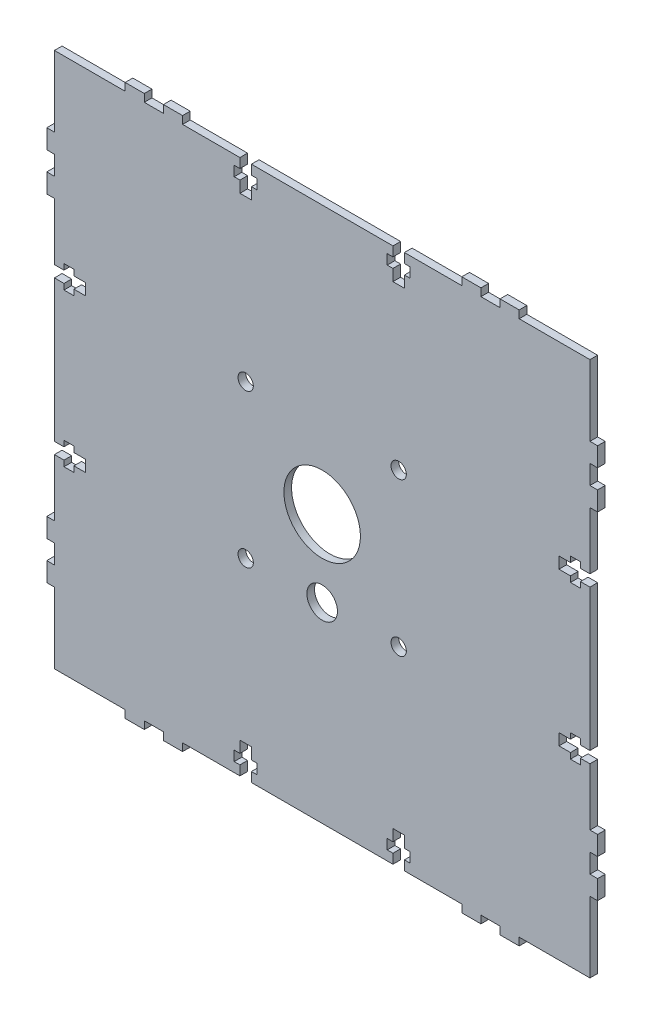
SolidWorks part; units mm, degrees
ref_plane "前视基准面" through (0, 0, 0) normal (0, 0, 1) x (1, 0, 0)
ref_plane "上视基准面" through (0, 0, 0) normal (0, 1, 0) x (1, 0, 0)
ref_plane "右视基准面" through (0, 0, 0) normal (1, 0, 0) x (0, 0, -1)
sketch "草图1" plane through (0, 0, 0) normal (0, 0, 1) x (1, 0, 0)
  line L50 (249.9534, 275.9629) -> (249.9534, 255.9629) construction
  line L53 (317.4534, 257.4629) -> (317.4534, 258.9629)
  line L54 (317.4534, 254.4629) -> (317.4534, 252.9629)
  line L55 (319.9534, 254.4629) -> (317.4534, 254.4629)
  line L56 (317.4534, 258.9629) -> (314.8534, 258.9629)
  line L57 (314.8534, 258.9629) -> (314.8534, 257.4629)
  line L58 (314.8534, 257.4629) -> (311.8534, 257.4629)
  line L59 (311.8534, 254.4629) -> (311.8534, 257.4629)
  line L60 (314.8534, 254.4629) -> (311.8534, 254.4629)
  line L61 (314.8534, 252.9629) -> (314.8534, 254.4629)
  line L62 (317.4534, 252.9629) -> (314.8534, 252.9629)
  line L63 (317.4534, 257.4629) -> (319.9534, 257.4629)
  line L68 (319.9534, 254.4629) -> (319.9534, 257.4629) construction
  line L69 (311.8534, 255.9629) -> (319.9534, 255.9629) construction
  line L73 (311.8534, 295.9629) -> (319.9534, 295.9629) construction
  line L75 (317.4534, 294.4629) -> (319.9534, 294.4629)
  line L76 (317.4534, 298.9629) -> (314.8534, 298.9629)
  line L77 (314.8534, 298.9629) -> (314.8534, 297.4629)
  line L78 (314.8534, 297.4629) -> (311.8534, 297.4629)
  line L79 (311.8534, 297.4629) -> (311.8534, 294.4629)
  line L80 (314.8534, 294.4629) -> (311.8534, 294.4629)
  line L81 (314.8534, 292.9629) -> (314.8534, 294.4629)
  line L82 (317.4534, 292.9629) -> (314.8534, 292.9629)
  line L83 (319.9534, 297.4629) -> (317.4534, 297.4629)
  line L84 (317.4534, 297.4629) -> (317.4534, 298.9629)
  line L85 (317.4534, 294.4629) -> (317.4534, 292.9629)
  line L86 (231.4534, 208.4629) -> (232.9534, 208.4629)
  line L87 (228.4534, 208.4629) -> (226.9534, 208.4629)
  line L88 (228.4534, 205.9629) -> (228.4534, 208.4629)
  line L89 (232.9534, 208.4629) -> (232.9534, 211.0629)
  line L90 (232.9534, 211.0629) -> (231.4534, 211.0629)
  line L91 (231.4534, 211.0629) -> (231.4534, 214.0629)
  line L92 (228.4534, 214.0629) -> (231.4534, 214.0629)
  line L93 (228.4534, 211.0629) -> (228.4534, 214.0629)
  line L94 (226.9534, 211.0629) -> (228.4534, 211.0629)
  line L95 (226.9534, 208.4629) -> (226.9534, 211.0629)
  line L96 (231.4534, 208.4629) -> (231.4534, 205.9629)
  line L97 (268.4534, 208.4629) -> (268.4534, 205.9629)
  line L98 (272.9534, 208.4629) -> (272.9534, 211.0629)
  line L99 (272.9534, 211.0629) -> (271.4534, 211.0629)
  line L100 (271.4534, 211.0629) -> (271.4534, 214.0629)
  line L101 (271.4534, 214.0629) -> (268.4534, 214.0629)
  line L102 (268.4534, 211.0629) -> (268.4534, 214.0629)
  line L103 (266.9534, 211.0629) -> (268.4534, 211.0629)
  line L104 (266.9534, 208.4629) -> (266.9534, 211.0629)
  line L105 (271.4534, 205.9629) -> (271.4534, 208.4629)
  line L106 (271.4534, 208.4629) -> (272.9534, 208.4629)
  line L107 (268.4534, 208.4629) -> (266.9534, 208.4629)
  line L108 (228.4534, 205.9629) -> (231.4534, 205.9629) construction
  line L109 (229.9534, 214.0629) -> (229.9534, 205.9629) construction
  line L110 (269.9534, 214.0629) -> (269.9534, 205.9629) construction
  line L111 (182.4534, 294.4629) -> (182.4534, 292.9629)
  line L112 (182.4534, 297.4629) -> (182.4534, 298.9629)
  line L113 (179.9534, 297.4629) -> (182.4534, 297.4629)
  line L114 (182.4534, 292.9629) -> (185.0534, 292.9629)
  line L115 (185.0534, 292.9629) -> (185.0534, 294.4629)
  line L116 (185.0534, 294.4629) -> (188.0534, 294.4629)
  line L117 (188.0534, 297.4629) -> (188.0534, 294.4629)
  line L118 (185.0534, 297.4629) -> (188.0534, 297.4629)
  line L119 (185.0534, 298.9629) -> (185.0534, 297.4629)
  line L120 (182.4534, 298.9629) -> (185.0534, 298.9629)
  line L121 (182.4534, 294.4629) -> (179.9534, 294.4629)
  line L122 (182.4534, 257.4629) -> (179.9534, 257.4629)
  line L123 (182.4534, 252.9629) -> (185.0534, 252.9629)
  line L124 (185.0534, 252.9629) -> (185.0534, 254.4629)
  line L125 (185.0534, 254.4629) -> (188.0534, 254.4629)
  line L126 (188.0534, 254.4629) -> (188.0534, 257.4629)
  line L127 (185.0534, 257.4629) -> (188.0534, 257.4629)
  line L128 (185.0534, 258.9629) -> (185.0534, 257.4629)
  line L129 (182.4534, 258.9629) -> (185.0534, 258.9629)
  line L130 (179.9534, 254.4629) -> (182.4534, 254.4629)
  line L131 (182.4534, 254.4629) -> (182.4534, 252.9629)
  line L132 (182.4534, 257.4629) -> (182.4534, 258.9629)
  line L133 (179.9534, 297.4629) -> (179.9534, 294.4629) construction
  line L134 (188.0534, 295.9629) -> (179.9534, 295.9629) construction
  line L135 (188.0534, 255.9629) -> (179.9534, 255.9629) construction
  line L136 (268.4534, 343.4629) -> (266.9534, 343.4629)
  line L137 (271.4534, 343.4629) -> (272.9534, 343.4629)
  line L138 (271.4534, 345.9629) -> (271.4534, 343.4629)
  line L139 (266.9534, 343.4629) -> (266.9534, 340.8629)
  line L140 (266.9534, 340.8629) -> (268.4534, 340.8629)
  line L141 (268.4534, 340.8629) -> (268.4534, 337.8629)
  line L142 (271.4534, 337.8629) -> (268.4534, 337.8629)
  line L143 (271.4534, 340.8629) -> (271.4534, 337.8629)
  line L144 (272.9534, 340.8629) -> (271.4534, 340.8629)
  line L145 (272.9534, 343.4629) -> (272.9534, 340.8629)
  line L146 (268.4534, 343.4629) -> (268.4534, 345.9629)
  line L147 (231.4534, 343.4629) -> (231.4534, 345.9629)
  line L148 (226.9534, 343.4629) -> (226.9534, 340.8629)
  line L149 (226.9534, 340.8629) -> (228.4534, 340.8629)
  line L150 (228.4534, 340.8629) -> (228.4534, 337.8629)
  line L151 (228.4534, 337.8629) -> (231.4534, 337.8629)
  line L152 (231.4534, 340.8629) -> (231.4534, 337.8629)
  line L153 (232.9534, 340.8629) -> (231.4534, 340.8629)
  line L154 (232.9534, 343.4629) -> (232.9534, 340.8629)
  line L155 (228.4534, 345.9629) -> (228.4534, 343.4629)
  line L156 (228.4534, 343.4629) -> (226.9534, 343.4629)
  line L157 (231.4534, 343.4629) -> (232.9534, 343.4629)
  line L158 (271.4534, 345.9629) -> (268.4534, 345.9629) construction
  line L159 (269.9534, 337.8629) -> (269.9534, 345.9629) construction
  line L160 (229.9534, 337.8629) -> (229.9534, 345.9629) construction
  line L163 (179.9534, 294.4629) -> (179.9534, 257.4629)
  line L169 (268.4534, 345.9629) -> (231.4534, 345.9629)
  line L172 (319.9534, 257.4629) -> (319.9534, 294.4629)
  line L175 (231.4534, 205.9629) -> (268.4534, 205.9629)
  line L188 (179.9534, 239.4629) -> (177.9534, 239.4629)
  line L189 (177.9534, 239.4629) -> (177.9534, 234.4629)
  line L190 (177.9534, 234.4629) -> (179.9534, 234.4629)
  line L191 (179.9534, 234.4629) -> (179.9534, 229.4629)
  line L192 (179.9534, 229.4629) -> (177.9534, 229.4629)
  line L193 (177.9534, 229.4629) -> (177.9534, 224.4629)
  line L194 (177.9534, 224.4629) -> (179.9534, 224.4629)
  line L195 (179.9534, 224.4629) -> (179.9534, 205.9629)
  line L196 (179.9534, 327.4629) -> (179.9534, 345.9629)
  line L197 (177.9534, 327.4629) -> (179.9534, 327.4629)
  line L198 (177.9534, 322.4629) -> (177.9534, 327.4629)
  line L199 (179.9534, 322.4629) -> (177.9534, 322.4629)
  line L200 (179.9534, 317.4629) -> (179.9534, 322.4629)
  line L201 (177.9534, 317.4629) -> (179.9534, 317.4629)
  line L202 (177.9534, 312.4629) -> (177.9534, 317.4629)
  line L203 (179.9534, 312.4629) -> (177.9534, 312.4629)
  line L206 (213.4534, 345.9629) -> (213.4534, 347.9629)
  line L207 (213.4534, 347.9629) -> (208.4534, 347.9629)
  line L208 (208.4534, 347.9629) -> (208.4534, 345.9629)
  line L209 (208.4534, 345.9629) -> (203.4534, 345.9629)
  line L210 (203.4534, 345.9629) -> (203.4534, 347.9629)
  line L211 (203.4534, 347.9629) -> (198.4534, 347.9629)
  line L212 (198.4534, 347.9629) -> (198.4534, 345.9629)
  line L213 (198.4534, 345.9629) -> (179.9534, 345.9629)
  line L214 (301.4534, 345.9629) -> (319.9534, 345.9629)
  line L215 (301.4534, 347.9629) -> (301.4534, 345.9629)
  line L216 (296.4534, 347.9629) -> (301.4534, 347.9629)
  line L217 (296.4534, 345.9629) -> (296.4534, 347.9629)
  line L218 (291.4534, 345.9629) -> (296.4534, 345.9629)
  line L219 (291.4534, 347.9629) -> (291.4534, 345.9629)
  line L220 (286.4534, 347.9629) -> (291.4534, 347.9629)
  line L221 (286.4534, 345.9629) -> (286.4534, 347.9629)
  line L224 (319.9534, 312.4629) -> (321.9534, 312.4629)
  line L225 (321.9534, 312.4629) -> (321.9534, 317.4629)
  line L226 (321.9534, 317.4629) -> (319.9534, 317.4629)
  line L227 (319.9534, 317.4629) -> (319.9534, 322.4629)
  line L228 (319.9534, 322.4629) -> (321.9534, 322.4629)
  line L229 (321.9534, 322.4629) -> (321.9534, 327.4629)
  line L230 (321.9534, 327.4629) -> (319.9534, 327.4629)
  line L231 (319.9534, 327.4629) -> (319.9534, 345.9629)
  line L232 (319.9534, 224.4629) -> (319.9534, 205.9629)
  line L233 (321.9534, 224.4629) -> (319.9534, 224.4629)
  line L234 (321.9534, 229.4629) -> (321.9534, 224.4629)
  line L235 (319.9534, 229.4629) -> (321.9534, 229.4629)
  line L236 (319.9534, 234.4629) -> (319.9534, 229.4629)
  line L237 (321.9534, 234.4629) -> (319.9534, 234.4629)
  line L238 (321.9534, 239.4629) -> (321.9534, 234.4629)
  line L239 (319.9534, 239.4629) -> (321.9534, 239.4629)
  line L242 (286.4534, 205.9629) -> (286.4534, 203.9629)
  line L243 (286.4534, 203.9629) -> (291.4534, 203.9629)
  line L244 (291.4534, 203.9629) -> (291.4534, 205.9629)
  line L245 (291.4534, 205.9629) -> (296.4534, 205.9629)
  line L246 (296.4534, 205.9629) -> (296.4534, 203.9629)
  line L247 (296.4534, 203.9629) -> (301.4534, 203.9629)
  line L248 (301.4534, 203.9629) -> (301.4534, 205.9629)
  line L249 (301.4534, 205.9629) -> (319.9534, 205.9629)
  line L250 (198.4534, 205.9629) -> (179.9534, 205.9629)
  line L251 (198.4534, 203.9629) -> (198.4534, 205.9629)
  line L252 (203.4534, 203.9629) -> (198.4534, 203.9629)
  line L253 (203.4534, 205.9629) -> (203.4534, 203.9629)
  line L254 (208.4534, 205.9629) -> (203.4534, 205.9629)
  line L255 (208.4534, 203.9629) -> (208.4534, 205.9629)
  line L256 (213.4534, 203.9629) -> (208.4534, 203.9629)
  line L257 (213.4534, 205.9629) -> (213.4534, 203.9629)
  line L261 (249.9534, 255.9629) -> (229.9534, 255.9629) construction
  line L268 (179.9534, 297.4629) -> (179.9534, 312.4629)
  line L269 (213.4534, 345.9629) -> (228.4534, 345.9629)
  line L270 (271.4534, 345.9629) -> (286.4534, 345.9629)
  line L271 (319.9534, 312.4629) -> (319.9534, 297.4629)
  line L272 (319.9534, 254.4629) -> (319.9534, 239.4629)
  line L273 (286.4534, 205.9629) -> (271.4534, 205.9629)
  line L274 (213.4534, 205.9629) -> (228.4534, 205.9629)
  line L275 (179.9534, 239.4629) -> (179.9534, 254.4629)
  circle A14 centre (249.9534, 275.9629) radius 10
  circle A24 centre (249.9534, 255.9629) radius 4
  circle A29 centre (229.9534, 255.9629) radius 2
  circle A30 centre (229.9534, 295.9629) radius 2
  circle A31 centre (269.9534, 295.9629) radius 2
  circle A32 centre (269.9534, 255.9629) radius 2
  dimension "D5" = 4
  dimension "D4" = 4
extrude "凸台-拉伸1" add sketch "草图1" along normal blind 2
sketch "草图2" plane through (179.9534, 0, 0) normal (-1, 0, 0) x (0, 0, 1)
  line L0 (1, 294.4629) -> (1, 297.4629) construction
  line L1 (2, 294.4629) -> (0, 294.4629) construction
  line L2 (2, 297.4629) -> (0, 297.4629) construction
  line L3 (1, 295.9629) -> (1, 312.4629) construction
  line L4 (2, 312.4629) -> (0, 312.4629) construction
  circle A0 centre (1, 295.9629) radius 1.5
sketch "草图3" plane through (0, 345.9629, 0) normal (0, 1, 0) x (1, 0, 0)
  line L0 (228.4534, -1) -> (231.4534, -1)
  line L1 (228.4534, -2) -> (228.4534, 0) construction
  line L2 (231.4534, -2) -> (231.4534, 0) construction
  circle A0 centre (229.9534, -1) radius 1.5
sketch "草图4" plane through (319.9534, 0, 0) normal (1, 0, 0) x (0, 0, -1)
  line L0 (-1, 257.4629) -> (-1, 254.4629) construction
  line L1 (-2, 257.4629) -> (0, 257.4629) construction
  line L2 (-2, 254.4629) -> (0, 254.4629) construction
  circle A0 centre (-1, 255.9629) radius 1.5
sketch "草图5" plane through (0, 205.9629, 0) normal (0, -1, 0) x (1, 0, 0)
  line L0 (231.4534, 1) -> (228.4534, 1) construction
  line L1 (231.4534, 2) -> (231.4534, 0) construction
  line L2 (228.4534, 2) -> (228.4534, 0) construction
  circle A0 centre (229.9534, 1) radius 1.5
